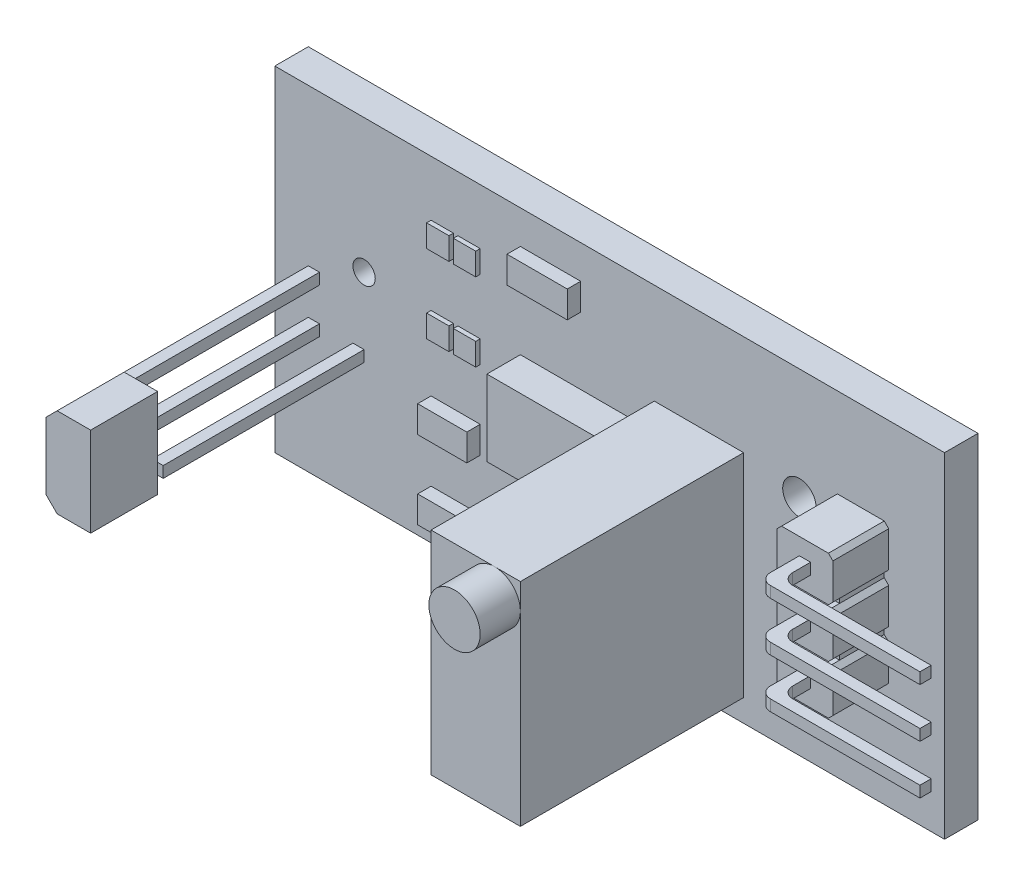
SolidWorks part; units mm, degrees
ref_plane "前视基准面" through (0, 0, 0) normal (0, 0, 1) x (1, 0, 0)
ref_plane "上视基准面" through (0, 0, 0) normal (0, 1, 0) x (1, 0, 0)
ref_plane "右视基准面" through (0, 0, 0) normal (1, 0, 0) x (0, 0, -1)
sketch "草图1" plane through (0, 0, 0) normal (0, 0, 1) x (1, 0, 0)
  line L1 (0, 0) -> (30, 0)
  line L2 (0, 0) -> (0, 15)
  line L3 (0, 15) -> (30, 15)
  line L4 (30, 0) -> (30, 15)
  dimension "D1" = 30
  dimension "D2" = 15
extrude "凸台-拉伸1" add sketch "草图1" along normal blind 1.5
sketch "草图2" plane through (0, 0, 1.5) normal (0, 0, 1) x (1, 0, 0)
  line L0 (30, 0) -> (30, 15) construction
  line L1 (17, 10.5) -> (21, 10.5)
  line L2 (17, 10.5) -> (17, 1)
  line L3 (17, 1) -> (21, 1)
  line L4 (21, 10.5) -> (21, 1)
  line L5 (30, 15) -> (0, 15) construction
  point P8 (19, 1)
  dimension "D1" = 13
  dimension "D2" = 4
  dimension "D3" = 14
  dimension "D4" = 9.5
extrude "凸台-拉伸2" add sketch "草图2" along normal blind 10
sketch "草图3" plane through (0, 0, 11.5) normal (0, 0, 1) x (1, 0, 0)
  line L0 (21, 10.5) -> (17, 10.5) construction
  line L1 (21, 1) -> (21, 10.5) construction
  circle A0 centre (19.85, 9.35) radius 1.15
  dimension "D1" = 2.3
extrude "凸台-拉伸3" add sketch "草图3" along normal blind 1.8
sketch "草图5" plane through (0, 0, 1.5) normal (0, 0, 1) x (1, 0, 0)
  line L0 (30, 15) -> (0, 15) construction
  line L1 (25, 11) -> (27.5, 11)
  line L2 (25, 11) -> (25, 9)
  line L3 (25, 9) -> (27.5, 9)
  line L4 (27.5, 11) -> (27.5, 9)
  line L5 (30, 0) -> (30, 15) construction
  line L6 (25, 8.8) -> (25, 6.8)
  line L7 (25, 8.8) -> (27.5, 8.8)
  line L8 (27.5, 8.8) -> (27.5, 6.8)
  line L9 (25, 6.8) -> (27.5, 6.8)
  line L10 (25, 6.6) -> (25, 4.6)
  line L11 (25, 6.6) -> (27.5, 6.6)
  line L12 (27.5, 6.6) -> (27.5, 4.6)
  line L13 (25, 4.6) -> (27.5, 4.6)
  dimension "D1" = 4
  dimension "D2" = 5
  dimension "D3" = 2.5
  dimension "D4" = 2
  dimension "D6" = 2.2
  dimension "D5" = 3
extrude "凸台-拉伸4" add sketch "草图5" along normal blind 2.5
chamfer "倒角1" distance 0.2 12 edges at (25, 8.8, 2.75) (25, 9, 2.75) (25, 11, 2.75) (27.5, 11, 2.75) (27.5, 9, 2.75) (27.5, 8.8, 2.75) (27.5, 6.8, 2.75) (25, 6.8, 2.75) (25, 6.6, 2.75) (25, 4.6, 2.75) (27.5, 6.6, 2.75) (27.5, 4.6, 2.75)
sketch "草图6" plane through (0, 0, 1.5) normal (0, 0, 1) x (1, 0, 0)
  line L0 (27.3, 6.6) -> (27.5, 6.4) construction
  line L1 (25.2, 9) -> (27.3, 9)
  line L2 (25.2, 9) -> (25.2, 8.8)
  line L3 (25.2, 8.8) -> (27.3, 8.8)
  line L4 (27.3, 9) -> (27.3, 8.8)
  line L5 (25.2, 6.8) -> (27.3, 6.8)
  line L6 (25.2, 6.8) -> (25.2, 6.6)
  line L7 (25.2, 6.6) -> (27.3, 6.6)
  line L8 (27.3, 6.8) -> (27.3, 6.6)
  line L9 (27.5, 6.4) -> (27.3, 6.6) construction
extrude "凸台-拉伸5" add sketch "草图6" along normal blind 2
sketch "草图7" plane through (0, 0, 4) normal (0, 0, 1) x (1, 0, 0)
  line L0 (25, 6.4) -> (25, 4.8) construction
  line L1 (26, 5.35) -> (26.5, 5.35)
  line L2 (26, 5.35) -> (26, 5.85)
  line L3 (26, 5.85) -> (26.5, 5.85)
  line L4 (26.5, 5.35) -> (26.5, 5.85)
  line L5 (25.2, 4.6) -> (27.3, 4.6) construction
  line L6 (26, 7.55) -> (26, 8.05)
  line L7 (26, 8.05) -> (26.5, 8.05)
  line L8 (26.5, 7.55) -> (26.5, 8.05)
  line L9 (26, 7.55) -> (26.5, 7.55)
  line L10 (26, 9.75) -> (26, 10.25)
  line L11 (26, 10.25) -> (26.5, 10.25)
  line L12 (26.5, 9.75) -> (26.5, 10.25)
  line L13 (26, 9.75) -> (26.5, 9.75)
  dimension "D1" = 0.5
  dimension "D2" = 1
  dimension "D3" = 0.75
  dimension "D4" = 0.5
  dimension "D6" = 2.2
  dimension "D5" = 3
extrude "凸台-拉伸6" add sketch "草图7" along normal blind 1.8
sketch "草图8" plane through (26.5, 0, 0) normal (1, 0, 0) x (0, 0, -1)
  line L0 (-5.8, 5.85) -> (-4, 5.85) construction
  line L1 (-5.8, 5.35) -> (-5.3, 5.35)
  line L2 (-5.8, 5.35) -> (-5.8, 5.85)
  line L3 (-5.8, 5.85) -> (-5.3, 5.85)
  line L4 (-5.3, 5.35) -> (-5.3, 5.85)
  line L5 (-5.8, 7.55) -> (-5.3, 7.55)
  line L6 (-5.8, 7.55) -> (-5.8, 8.05)
  line L7 (-5.8, 8.05) -> (-5.3, 8.05)
  line L8 (-5.3, 7.55) -> (-5.3, 8.05)
  line L9 (-5.8, 9.75) -> (-5.3, 9.75)
  line L10 (-5.8, 9.75) -> (-5.8, 10.25)
  line L11 (-5.8, 10.25) -> (-5.3, 10.25)
  line L12 (-5.3, 9.75) -> (-5.3, 10.25)
  dimension "D1" = 0.5
  dimension "D2" = 3
  dimension "D3" = 2.2
extrude "凸台-拉伸7" add sketch "草图8" along normal blind 6.7
fillet "圆角1" radius 0.5 6 edges at (26.5, 5.6, 5.3) (26, 5.6, 5.8) (26, 10, 5.8) (26.5, 10, 5.3) (26.5, 7.8, 5.3) (26, 7.8, 5.8)
sketch "草图10" plane through (0, 0, 1.5) normal (0, 0, 1) x (1, 0, 0)
  line L0 (30, 15) -> (0, 15) construction
  line L1 (30, 0) -> (30, 15) construction
  circle A0 centre (23.5, 10) radius 0.748
  circle A1 centre (23.5, 7.8) radius 0.748
  circle A2 centre (23.5, 5.6) radius 0.748
  dimension "D1" = 5
  dimension "D2" = 1.496
  dimension "D5" = 2.2
  dimension "D3" = 6.5
  dimension "D4" = 3
extrude "切除-拉伸1" cut sketch "草图10" against normal through all
sketch "草图11" plane through (0, 0, 1.5) normal (0, 0, 1) x (1, 0, 0)
  line L0 (30, 0) -> (30, 15) construction
  line L1 (11, 9.3) -> (16, 9.3)
  line L2 (11, 9.3) -> (11, 5.9)
  line L3 (11, 5.9) -> (16, 5.9)
  line L4 (16, 9.3) -> (16, 5.9)
  line L5 (30, 15) -> (0, 15) construction
  dimension "D1" = 19
  dimension "D2" = 5
  dimension "D3" = 3.4
  dimension "D4" = 5.7
extrude "凸台-拉伸8" add sketch "草图11" along normal blind 1.5
sketch "草图12" plane through (0, 0, 1.5) normal (0, 0, 1) x (1, 0, 0)
  line L0 (30, 0) -> (30, 15) construction
  line L1 (11, 13.5) -> (13.7, 13.5)
  line L2 (11, 13.5) -> (11, 12.3)
  line L3 (11, 12.3) -> (13.7, 12.3)
  line L4 (13.7, 13.5) -> (13.7, 12.3)
  line L5 (30, 15) -> (0, 15) construction
  dimension "D1" = 19
  dimension "D2" = 2.7
  dimension "D3" = 2.7
  dimension "D4" = 1.2
extrude "凸台-拉伸9" add sketch "草图12" along normal blind 0.6
sketch "草图13" plane through (0, 0, 1.5) normal (0, 0, 1) x (1, 0, 0)
  line L0 (30, 0) -> (30, 15) construction
  line L1 (11, 2.3) -> (12.6, 2.3)
  line L2 (11, 2.3) -> (11, 1)
  line L3 (11, 1) -> (12.6, 1)
  line L4 (12.6, 2.3) -> (12.6, 1)
  line L5 (30, 15) -> (0, 15) construction
  dimension "D1" = 19
  dimension "D2" = 14
  dimension "D3" = 1.3
  dimension "D4" = 1.6
extrude "凸台-拉伸10" add sketch "草图13" along normal blind 1
sketch "草图14" plane through (0, 0, 1.5) normal (0, 0, 1) x (1, 0, 0)
  line L0 (30, 0) -> (30, 15) construction
  line L1 (7, 12.517) -> (8, 12.517)
  line L2 (7, 12.517) -> (7, 11.517)
  line L3 (7, 11.517) -> (8, 11.517)
  line L4 (8, 12.517) -> (8, 11.517)
  line L5 (30, 15) -> (0, 15) construction
  line L6 (8.2, 12.517) -> (9.2, 12.517)
  line L7 (9.2, 12.517) -> (9.2, 11.517)
  line L8 (8.2, 11.517) -> (9.2, 11.517)
  line L9 (8.2, 12.517) -> (8.2, 11.517)
  line L10 (8.2, 9.017) -> (9.2, 9.017)
  line L11 (9.2, 9.017) -> (9.2, 8.017)
  line L12 (8.2, 8.017) -> (9.2, 8.017)
  line L13 (8.2, 9.017) -> (8.2, 8.017)
  line L14 (7, 9.017) -> (8, 9.017)
  line L15 (8, 9.017) -> (8, 8.017)
  line L16 (7, 8.017) -> (8, 8.017)
  line L17 (7, 9.017) -> (7, 8.017)
  dimension "D1" = 23
  dimension "D2" = 1
  dimension "D3" = 3.483
  dimension "D4" = 2
  dimension "D6" = 1.2
  dimension "D7" = 3.5
  dimension "D5" = 2
extrude "凸台-拉伸11" add sketch "草图14" along normal blind 0.2
sketch "草图15" plane through (0, 0, 1.5) normal (0, 0, 1) x (1, 0, 0)
  line L0 (30, 0) -> (30, 15) construction
  line L1 (7, 5.7) -> (9.2, 5.7)
  line L2 (7, 5.7) -> (7, 4.5)
  line L3 (7, 4.5) -> (9.2, 4.5)
  line L4 (9.2, 5.7) -> (9.2, 4.5)
  line L5 (30, 15) -> (0, 15) construction
  line L6 (7, 2.2) -> (9.2, 2.2)
  line L7 (9.2, 2.2) -> (9.2, 1)
  line L8 (7, 2.2) -> (7, 1)
  line L9 (7, 1) -> (9.2, 1)
  dimension "D1" = 2.2
  dimension "D2" = 1.2
  dimension "D3" = 23
  dimension "D4" = 10.5
  dimension "D6" = 3.5
  dimension "D5" = 2
extrude "凸台-拉伸12" add sketch "草图15" along normal blind 0.6
sketch "草图17" plane through (0, 0, 1.5) normal (0, 0, 1) x (1, 0, 0)
  line L0 (30, 15) -> (0, 15) construction
  line L1 (30, 0) -> (30, 15) construction
  circle A0 centre (4, 9) radius 0.5
  dimension "D1" = 6
  dimension "D2" = 1
  dimension "D3" = 26
extrude "切除-拉伸2" cut sketch "草图17" against normal through all
sketch "草图18" plane through (0, 0, 1.5) normal (0, 0, 1) x (1, 0, 0)
  line L0 (30, 0) -> (30, 15) construction
  line L1 (3.5, 6) -> (4, 6)
  line L2 (3.5, 6) -> (3.5, 5.5)
  line L3 (3.5, 5.5) -> (4, 5.5)
  line L4 (4, 6) -> (4, 5.5)
  line L5 (1.5, 8) -> (2, 8)
  line L6 (1.5, 8) -> (1.5, 7.5)
  line L7 (1.5, 7.5) -> (2, 7.5)
  line L8 (2, 8) -> (2, 7.5)
  line L9 (1.5, 6) -> (2, 6)
  line L10 (1.5, 6) -> (1.5, 5.5)
  line L11 (1.5, 5.5) -> (2, 5.5)
  line L12 (2, 6) -> (2, 5.5)
  line L13 (30, 15) -> (0, 15) construction
  dimension "D1" = 26.5
  dimension "D2" = 0.5
  dimension "D3" = 9.5
  dimension "D4" = 0.5
  dimension "D5" = 2
  dimension "D6" = 0.5
  dimension "D7" = 7.5
  dimension "D8" = 0.5
extrude "凸台-拉伸13" add sketch "草图18" along normal blind 9
sketch "草图20" plane through (0, 0, 10.5) normal (0, 0, 1) x (1, 0, 0)
  line L0 (1.5, 8) -> (1.5, 5.5) construction
  line L1 (4, 5.5) -> (4, 7.8028) construction
  line L2 (1.5, 6.75) -> (4, 6.75) construction
  line L4 (1.75, 8.75) -> (3.75, 8.75)
  line L5 (1.75, 8.75) -> (1.75, 4.75)
  line L6 (1.75, 4.75) -> (3.75, 4.75)
  line L7 (3.75, 8.75) -> (3.75, 4.75)
  line L8 (1.75, 8.75) -> (3.75, 4.75) construction
  line L9 (1.75, 4.75) -> (3.75, 8.75) construction
  point P7 (2.75, 6.75)
  dimension "D1" = 4
  dimension "D2" = 2
extrude "凸台-拉伸14" add sketch "草图20" along normal blind 3
chamfer "倒角2" distance 0.5 angle 45 2 edges at (1.75, 8.75, 12) (1.75, 4.75, 12)
